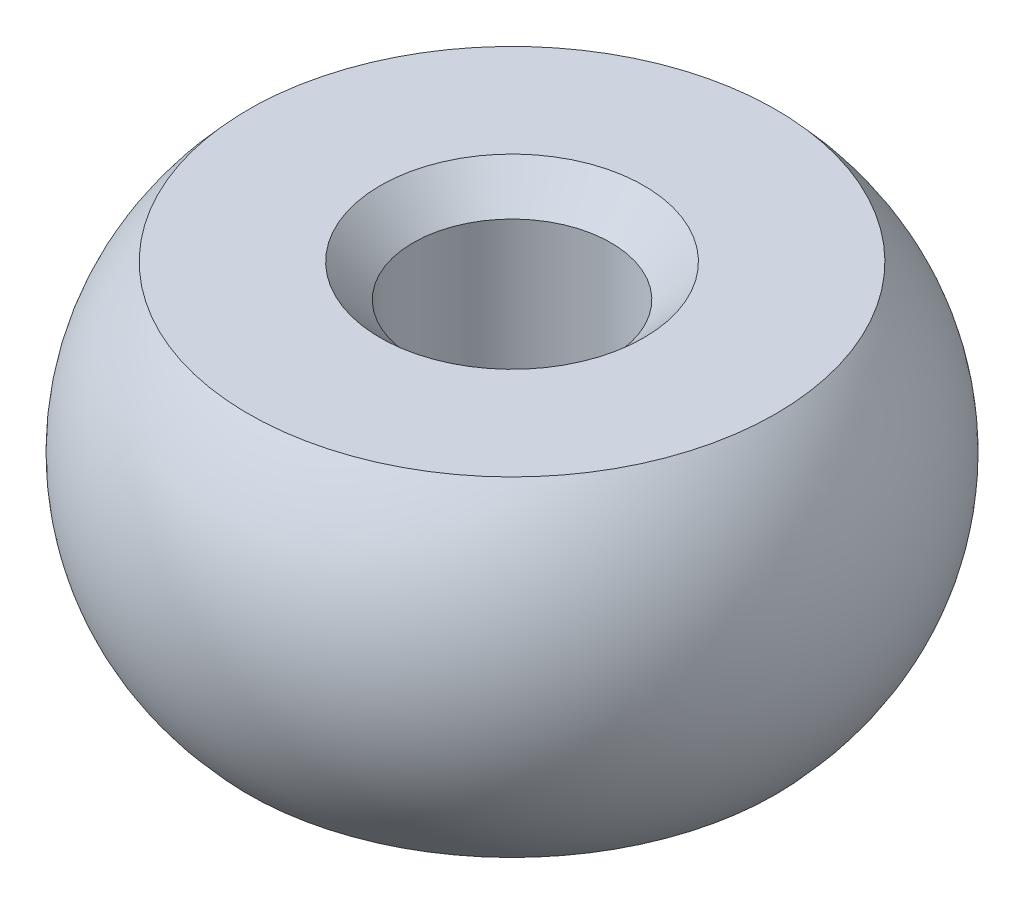
SolidWorks part; units mm, degrees
material "AISI Type A2 Tool Steel"
ref_plane "Front Plane" through (0, 0, 0) normal (0, 0, 1) x (1, 0, 0)
ref_plane "Top Plane" through (0, 0, 0) normal (0, 1, 0) x (1, 0, 0)
ref_plane "Right Plane" through (0, 0, 0) normal (1, 0, 0) x (0, 0, -1)
sketch "Sketch1" plane through (0, 0, 0) normal (0, 0, 1) x (1, 0, 0)
  line L0 (0, -90.7239) -> (0, 4445.4693) construction
  line L1 (1.5, 2.5) -> (1.5, -2.5)
  line L2 (1.5, 2.5) -> (4, 2.5)
  line L3 (1.5, -2.5) -> (4, -2.5)
  arc A1 (4, 2.5) -> (4, -2.5) centre (1.375, 0) cw
  point P5 (1.5, 0)
  point P6 (3.9511, 2.5)
  point P11 (5, 0)
  dimension "D3" = 10
  dimension "D4" = 2.5
  dimension "D1" = 5
  dimension "D2" = 3
revolve "Revolve1" add sketch "Sketch1" angle 360 about L0
chamfer "Chamfer1" distance 0.5 angle 45 2 edges at (1.5, 2.5, 0) (1.5, -2.5, 0)
